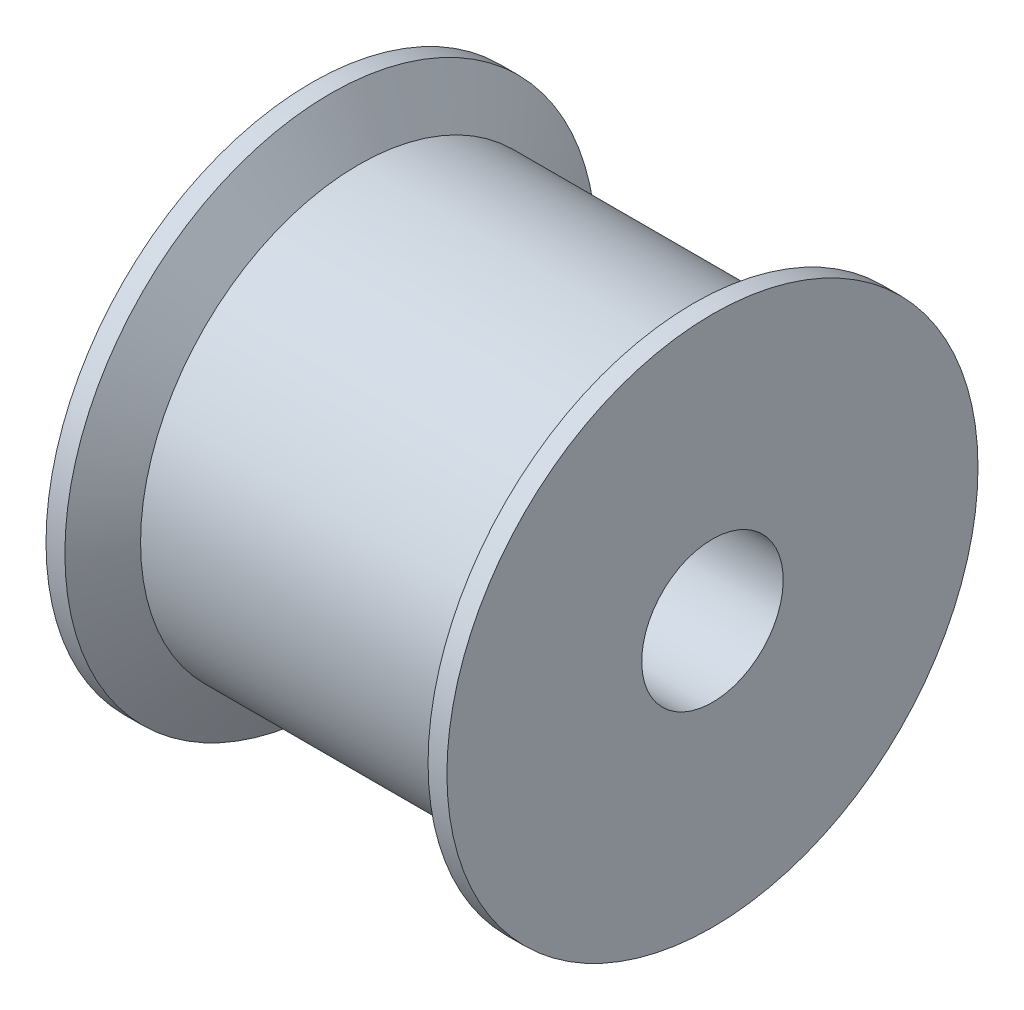
SolidWorks part; units mm, degrees
ref_plane "Front Plane" through (0, 0, 0) normal (0, 0, 1) x (1, 0, 0)
ref_plane "Top Plane" through (0, 0, 0) normal (0, 1, 0) x (1, 0, 0)
ref_plane "Right Plane" through (0, 0, 0) normal (1, 0, 0) x (0, 0, -1)
sketch "Sketch1" plane through (0, 0, 0) normal (0, 0, 1) x (1, 0, 0)
  line L0 (-8.5, 0.6052) -> (0, 0.6052)
  line L1 (-8.5, 0.6052) -> (-8.5, 4.7352)
  line L2 (-8.5, 4.7352) -> (-8.1, 4.7352)
  line L3 (-8.1, 4.7352) -> (-7.5, 3.7302)
  line L4 (-7.5, 3.7302) -> (-1, 3.7302)
  line L5 (-1, 3.7302) -> (-0.4, 4.7352)
  line L6 (-0.4, 4.7352) -> (0, 4.7352)
  line L7 (0, 4.7352) -> (0, 0.6052)
  line L10 (10.31, -0.8948) -> (-16.8969, -0.8948) construction
  dimension "D1" = 6.5
  dimension "D2" = 4.625
  dimension "D3" = 3
  dimension "D4" = 1
  dimension "D5" = 0.4
  dimension "D6" = 5.63
  dimension "D7" = 0.4
  dimension "D8" = 1
revolve "Revolve1" add sketch "Sketch1" angle 360 about L10
